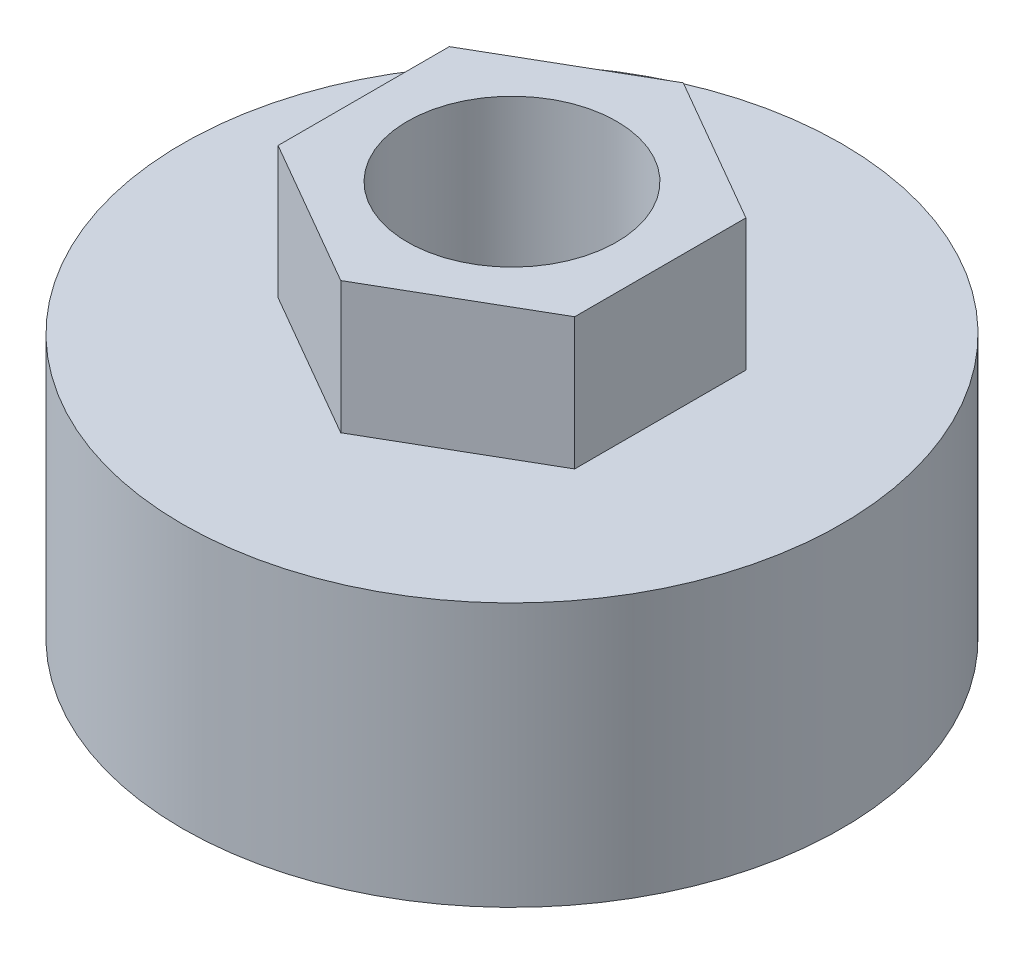
SolidWorks part; units mm, degrees
ref_plane "Front Plane" through (0, 0, 0) normal (0, 0, 1) x (1, 0, 0)
ref_plane "Top Plane" through (0, 0, 0) normal (0, 1, 0) x (1, 0, 0)
ref_plane "Right Plane" through (0, 0, 0) normal (1, 0, 0) x (0, 0, -1)
sketch "Sketch1" plane through (0, 0, 0) normal (0, 0, 1) x (1, 0, 0)
  line L3 (15.875, 0) -> (15.875, 12.7)
  line L7 (0, 0) -> (0, 63.6042) construction
  line L8 (5.0419, 0) -> (5.0419, 12.7)
  line L9 (5.0419, 0) -> (15.875, 0)
  line L10 (0, 0) -> (48.1845, 0) construction
  line L11 (5.0419, 12.7) -> (15.875, 12.7)
  dimension "D1" = 10.0838
  dimension "D3" = 31.75
  dimension "D7" = 12.7
revolve "Revolve1" add sketch "Sketch1" angle 360 about L7
sketch "Sketch3" plane through (0, 0, 0) normal (0, -1, 0) x (1, 0, 0)
  line L0 (0, 0) -> (0, 8.7988) construction
  line L1 (7.62, -4.3994) -> (7.62, 4.3994)
  line L2 (7.62, 4.3994) -> (0, 8.7988)
  line L3 (0, 8.7988) -> (-7.62, 4.3994)
  line L4 (-7.62, 4.3994) -> (-7.62, -4.3994)
  line L5 (-7.62, -4.3994) -> (0, -8.7988)
  line L6 (0, -8.7988) -> (7.62, -4.3994)
  circle A0 centre (0, 0) radius 7.62 construction
  dimension "D1" = 15.24
extrude "Cut-Extrude1" cut sketch "Sketch3" against normal blind 9.525
sketch "Sketch4" plane through (0, 12.7, 0) normal (0, 1, 0) x (1, 0, 0)
  line L0 (0, 0) -> (0, 8.2489) construction
  line L1 (0, 8.2489) -> (-7.1437, 4.1244)
  line L2 (-7.1437, 4.1244) -> (-7.1437, -4.1244)
  line L3 (-7.1437, -4.1244) -> (0, -8.2489)
  line L4 (0, -8.2489) -> (7.1437, -4.1244)
  line L5 (7.1437, -4.1244) -> (7.1437, 4.1244)
  line L6 (7.1437, 4.1244) -> (0, 8.2489)
  circle A0 centre (0, 0) radius 7.1437 construction
  dimension "D1" = 14.2875
extrude "Boss-Extrude1" add sketch "Sketch4" along normal blind 6.35
sketch "Sketch5" plane through (0, 12.7, 0) normal (0, -1, 0) x (1, 0, 0)
  circle A1 centre (0, 0) radius 5.0419
  circle A2 centre (0, 0) radius 5.0419
  dimension "D1" = 0
extrude "Cut-Extrude2" cut sketch "Sketch5" against normal through all
